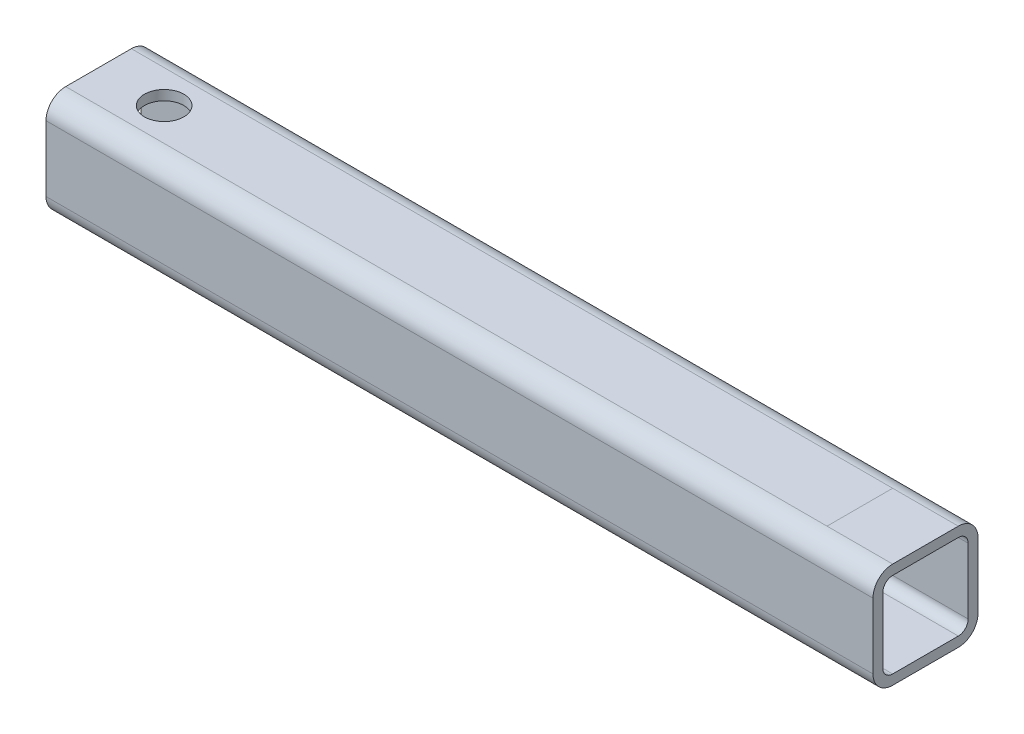
SolidWorks part; units mm, degrees
material "ASTM A36 Steel"
ref_plane "Front Plane" through (0, 0, 0) normal (0, 0, 1) x (1, 0, 0)
ref_plane "Top Plane" through (0, 0, 0) normal (0, 1, 0) x (1, 0, 0)
ref_plane "Right Plane" through (0, 0, 0) normal (1, 0, 0) x (0, 0, -1)
sketch "Sketch1" plane through (0, 0, 0) normal (0, 0, 1) x (1, 0, 0)
  line L0 (0, 0) -> (400, 0)
  dimension "D1" = 400
other "Tube square TS2X2X0.1875(1)"
ref_plane "Plane1" through (0, 0, 0) normal (1, 0, 0) x (0, 1, 0)
sketch "Sketch11" plane through (0, 0, 0) normal (1, 0, 0) x (0, 1, 0)
  line L0 (-15.875, -20.6375) -> (15.875, -20.6375)
  line L1 (-20.6375, -15.875) -> (-20.6375, 15.875)
  line L2 (15.875, 20.6375) -> (-15.875, 20.6375)
  line L3 (20.6375, 15.875) -> (20.6375, -15.875)
  line L4 (-15.875, -25.4) -> (15.875, -25.4)
  line L5 (-25.4, -15.875) -> (-25.4, 15.875)
  line L6 (15.875, 25.4) -> (-15.875, 25.4)
  line L7 (25.4, 15.875) -> (25.4, -15.875)
  line L8 (-25.4, 0) -> (-20.6375, 0) construction
  line L9 (-20.6375, 0) -> (20.6375, 0) construction
  line L10 (20.6375, 0) -> (25.4, 0) construction
  line L11 (0, 25.4) -> (0, 20.6375) construction
  line L12 (0, 20.6375) -> (0, -20.6375) construction
  line L13 (0, -20.6375) -> (0, -25.4) construction
  arc A0 (25.4, 15.875) -> (15.875, 25.4) centre (15.875, 15.875) ccw
  arc A1 (15.875, -25.4) -> (25.4, -15.875) centre (15.875, -15.875) ccw
  arc A2 (-25.4, -15.875) -> (-15.875, -25.4) centre (-15.875, -15.875) ccw
  arc A3 (-15.875, 25.4) -> (-25.4, 15.875) centre (-15.875, 15.875) ccw
  arc A4 (-15.875, 20.6375) -> (-20.6375, 15.875) centre (-15.875, 15.875) ccw
  arc A5 (20.6375, 15.875) -> (15.875, 20.6375) centre (15.875, 15.875) ccw
  arc A6 (15.875, -20.6375) -> (20.6375, -15.875) centre (15.875, -15.875) ccw
  arc A7 (-20.6375, -15.875) -> (-15.875, -20.6375) centre (-15.875, -15.875) ccw
  point P6 (-25.4, -25.4)
  point P33 (-25.4, 25.4)
  point P35 (25.4, 25.4)
  point P36 (25.4, -25.4)
  point P37 (0, 0)
  point P38 (0, 0)
  dimension "D1" = 9.525
  dimension "Thickness" = 4.7625
  dimension "V_leg" = 50.8
  dimension "H_leg" = 50.8
sketch "Sketch12" plane through (0, 25.4, 0) normal (0, 1, 0) x (1, 0, 0)
  line L0 (0, 0) -> (400, 0) construction
  circle A0 centre (31.75, 0) radius 9.525
  dimension "D2" = 19.05
  dimension "D1" = 31.75
extrude "Cut-Extrude1" cut sketch "Sketch12" against normal through all
sketch "Sketch13" plane through (0, 25.4, 0) normal (0, 1, 0) x (1, 0, 0)
  line L0 (400, -15.875) -> (0, -15.875) construction
  line L1 (400, 15.875) -> (368.25, 15.875)
  line L2 (400, 15.875) -> (400, -15.875)
  line L3 (400, -15.875) -> (368.25, -15.875)
  line L4 (368.25, 15.875) -> (368.25, -15.875)
split line "Split Line1"
